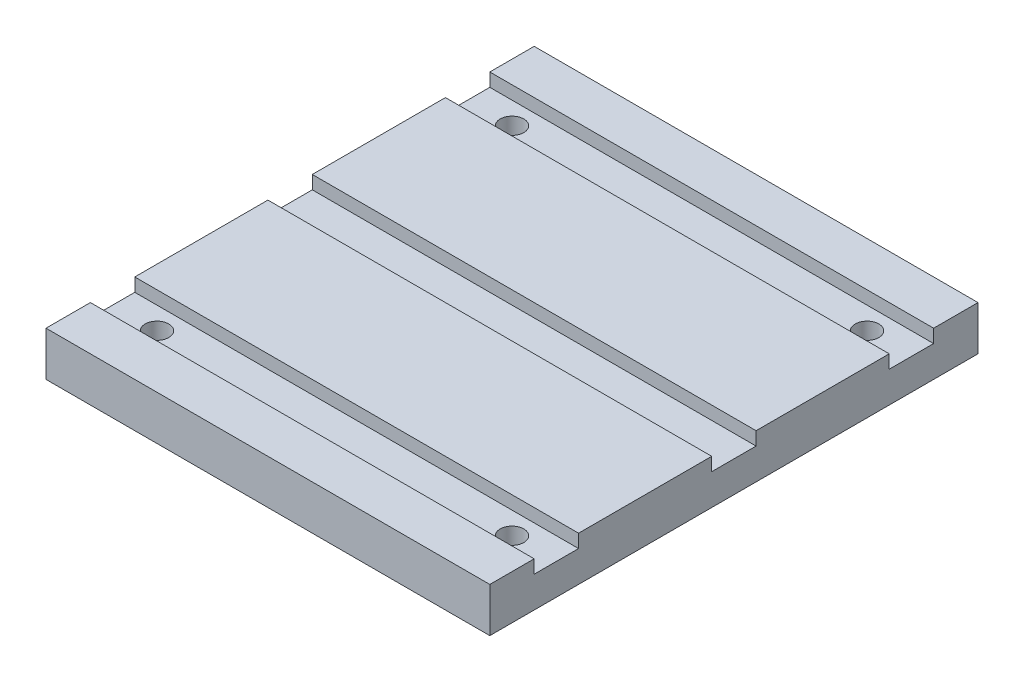
SolidWorks part; units mm, degrees
material "Acrylic (Medium-high impact)"
ref_plane "Front Plane" through (0, 0, 0) normal (0, 0, 1) x (1, 0, 0)
ref_plane "Top Plane" through (0, 0, 0) normal (0, 1, 0) x (1, 0, 0)
ref_plane "Right Plane" through (0, 0, 0) normal (1, 0, 0) x (0, 0, -1)
sketch "Sketch2" plane through (0, 0, 0) normal (0, 1, 0) x (1, 0, 0)
  line L1 (-63.5, 69.85) -> (63.5, 69.85)
  line L2 (-63.5, 69.85) -> (-63.5, -69.85)
  line L3 (-63.5, -69.85) -> (63.5, -69.85)
  line L4 (63.5, 69.85) -> (63.5, -69.85)
  line L5 (-63.5, 69.85) -> (63.5, -69.85) construction
  line L6 (-63.5, -69.85) -> (63.5, 69.85) construction
  point P0 (0, 0)
  dimension "D1" = 127
  dimension "D2" = 139.7
extrude "Boss-Extrude1" add sketch "Sketch2" along normal blind 12.7
sketch "Sketch4" plane through (63.5, 0, 0) normal (1, 0, 0) x (0, 0, -1)
  line L0 (-69.85, 12.7) -> (69.85, 12.7) construction
  line L1 (-57.15, 12.7) -> (-44.45, 12.7)
  line L2 (-57.15, 12.7) -> (-57.15, 8.89)
  line L3 (-57.15, 8.89) -> (-44.45, 8.89)
  line L4 (-44.45, 12.7) -> (-44.45, 8.89)
  line L5 (-69.85, 12.7) -> (-69.85, 0) construction
  dimension "D1" = 3.81
  dimension "D2" = 12.7
  dimension "D3" = 12.7
extrude "Cut-Extrude1" cut sketch "Sketch4" against normal blind 76.2
mirror "Mirror1" about plane through (0, 0, 0) normal (0, 0, 1) of "Cut-Extrude1"
sketch "Sketch5" plane through (63.5, 0, 0) normal (1, 0, 0) x (0, 0, -1)
  line L0 (-44.45, 12.7) -> (44.45, 12.7) construction
  line L1 (-6.35, 12.7) -> (6.35, 12.7)
  line L2 (-6.35, 12.7) -> (-6.35, 8.89)
  line L3 (-6.35, 8.89) -> (6.35, 8.89)
  line L4 (6.35, 12.7) -> (6.35, 8.89)
  point P6 (0, 8.89)
  dimension "D1" = 3.81
  dimension "D2" = 12.7
extrude "Cut-Extrude2" cut sketch "Sketch5" against normal blind 76.2
mirror "Mirror3" about plane through (0, 0, 0) normal (1, 0, 0) of "Cut-Extrude2", "Mirror1", "Cut-Extrude1"
sketch "Sketch6" plane through (0, 0, 0) normal (0, -1, 0) x (1, 0, 0)
  line L0 (0, 69.85) -> (0, -69.85) construction
  line L1 (-50.8, -50.8) -> (50.8, -50.8)
  line L2 (-50.8, -50.8) -> (-50.8, 50.8)
  line L3 (-50.8, 50.8) -> (50.8, 50.8)
  line L4 (50.8, -50.8) -> (50.8, 50.8)
  line L5 (-50.8, -50.8) -> (50.8, 50.8) construction
  line L6 (-50.8, 50.8) -> (50.8, -50.8) construction
  line L7 (-63.5, 69.85) -> (63.5, 69.85) construction
  line L8 (63.5, -69.85) -> (-63.5, -69.85) construction
  point P0 (0, 0)
  dimension "D1" = 101.6
  dimension "D2" = 101.6
hole_wizard "1/4 Clearance Hole1" positions "Sketch11" profile "Sketch12" hole size "1/4" standard "ANSI Inch" end condition through all
sketch "Sketch11" plane through (0, 0, 0) normal (0, -1, 0) x (-1, 0, 0)
  point P0 (-50.8, -50.8)
  point P3 (-50.8, 50.8)
  point P6 (50.8, 50.8)
  point P9 (50.8, -50.8)
sketch "Sketch12" plane through (50.8, 0, 50.8) normal (1, 0, 0) x (0, 0, -1)
  line L0 (0, 0) -> (0, 12.7)
  line L1 (0, 12.7) -> (3.3782, 12.7)
  line L2 (3.3782, 12.7) -> (3.3782, 0)
  line L5 (3.3782, 0) -> (0, 0)
  line L11 (0, -6.35) -> (0, 107.95) construction
  dimension "Thru Hole Dia." = 6.7564
  dimension "Thru Hole Depth" = 12.7
